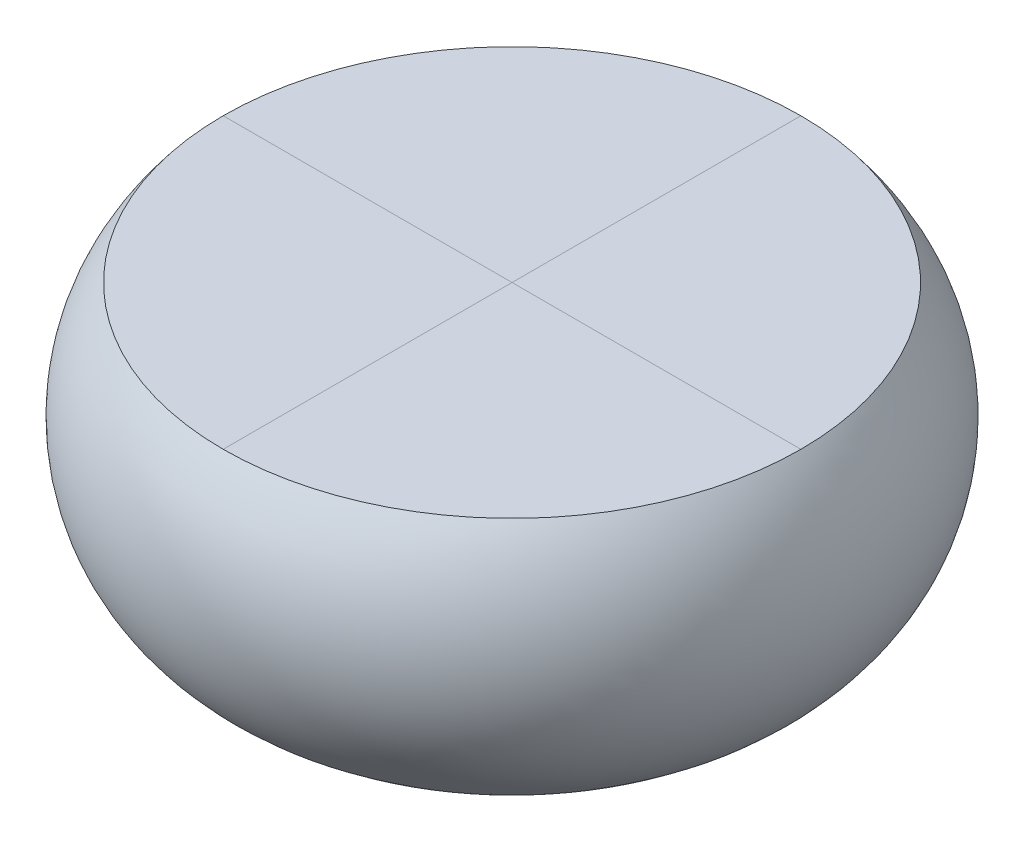
SolidWorks part; units mm, degrees
ref_plane "Front" through (0, 0, 0) normal (0, 0, 1) x (1, 0, 0)
ref_plane "Top" through (0, 0, 0) normal (0, 1, 0) x (1, 0, 0)
ref_plane "Right" through (0, 0, 0) normal (1, 0, 0) x (0, 0, -1)
other "Configuration Table"
sketch "Sketch1" plane through (0, 0, 0) normal (0, 0, 1) x (1, 0, 0)
  line L0 (0, 0) -> (70.9441, 0)
  line L1 (0, 197.0054) -> (0, -47.1361) construction
  line L2 (115.3502, 118.5941) -> (0, 118.5941)
  line L4 (0, 118.5941) -> (0, 0)
  arc A0 (70.9441, 0) -> (115.3502, 118.5941) centre (58.0136, 72.4524) ccw
  dimension "D1" = 70.9441
  dimension "D2" = 118.5941
  dimension "D3" = 115.3502
revolve "Revolve6" add sketch "Sketch1" angle 360 about L1
sketch "Sketch2" plane through (0, 118.5941, 0) normal (0, 1, 0) x (-1, 0, 0)
  line L0 (0, 163.675) -> (0, -159.9185)
split line "Split Line1"
sketch "Sketch3" plane through (0, 118.5941, 0) normal (0, 1, 0) x (-1, 0, 0)
  line L0 (-142.4777, 0) -> (140.8678, 0)
split line "Split Line2"
